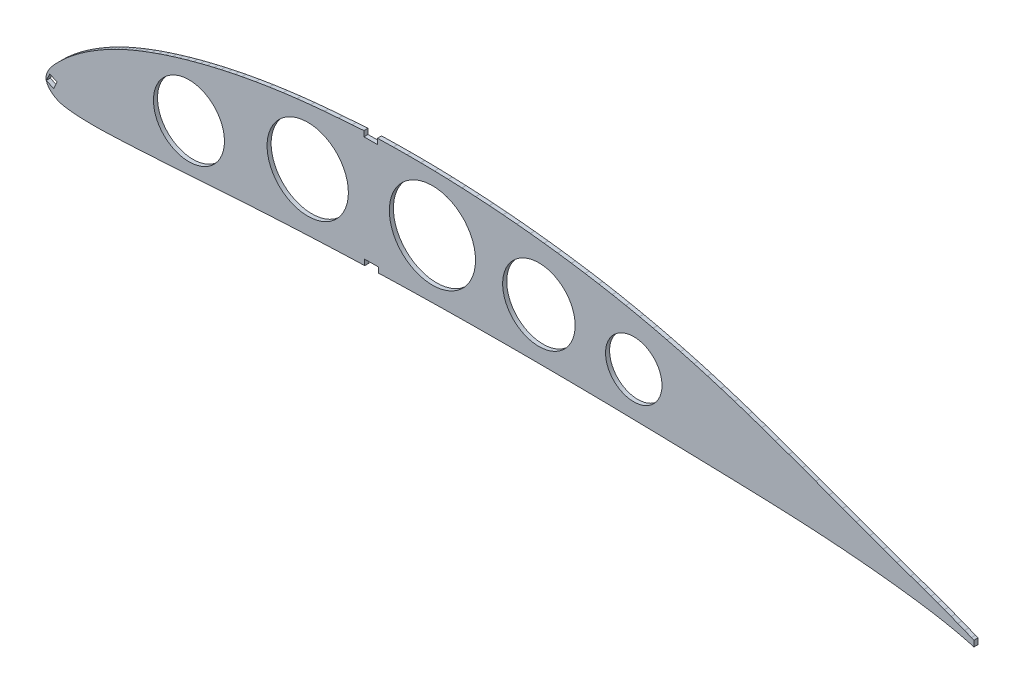
SolidWorks part; units mm, degrees
ref_plane "前视基准面" through (0, 0, 0) normal (0, 0, 1) x (1, 0, 0)
ref_plane "上视基准面" through (0, 0, 0) normal (0, 1, 0) x (1, 0, 0)
ref_plane "右视基准面" through (0, 0, 0) normal (1, 0, 0) x (0, 0, -1)
sketch "Model" plane through (0, 0, 0) normal (0, 0, 1) x (1, 0, 0)
  line L0 (1316.8722, -1.8169) -> (1315.9367, -1.4179)
  line L1 (1315.9367, -1.4179) -> (1313.4384, -0.3986)
  line L2 (1313.4384, -0.3986) -> (1310.9303, 0.599)
  line L3 (1310.9303, 0.599) -> (1308.4518, 1.5565)
  line L4 (1308.4518, 1.5565) -> (1305.9665, 2.4943)
  line L5 (1305.9665, 2.4943) -> (1303.4746, 3.4153)
  line L6 (1303.4746, 3.4153) -> (1300.9782, 4.3234)
  line L7 (1300.9782, 4.3234) -> (1298.4785, 5.2226)
  line L8 (1298.4785, 5.2226) -> (1295.9776, 6.1189)
  line L9 (1295.9776, 6.1189) -> (1293.4748, 7.0143)
  line L10 (1293.4748, 7.0143) -> (1288.4765, 8.8157)
  line L11 (1288.4765, 8.8157) -> (1283.4846, 10.63)
  line L12 (1283.4846, 10.63) -> (1278.4971, 12.4531)
  line L13 (1278.4971, 12.4531) -> (1273.5139, 14.285)
  line L14 (1273.5139, 14.285) -> (1268.5309, 16.1209)
  line L15 (1268.5309, 16.1209) -> (1263.5479, 17.9588)
  line L16 (1263.5479, 17.9588) -> (1258.5629, 19.7958)
  line L17 (1258.5629, 19.7958) -> (1253.6014, 21.6189)
  line L18 (1253.6014, 21.6189) -> (1248.6354, 23.4282)
  line L19 (1248.6354, 23.4282) -> (1243.6635, 25.2137)
  line L20 (1243.6635, 25.2137) -> (1238.6795, 26.9676)
  line L21 (1238.6795, 26.9676) -> (1233.6818, 28.678)
  line L22 (1233.6818, 28.678) -> (1228.6653, 30.337)
  line L23 (1228.6653, 30.337) -> (1223.6274, 31.9348)
  line L24 (1223.6274, 31.9348) -> (1218.677, 33.4313)
  line L25 (1218.677, 33.4313) -> (1213.7069, 34.8574)
  line L26 (1213.7069, 34.8574) -> (1208.7173, 36.2133)
  line L27 (1208.7173, 36.2133) -> (1203.709, 37.4967)
  line L28 (1203.709, 37.4967) -> (1198.682, 38.7079)
  line L29 (1198.682, 38.7079) -> (1193.6383, 39.8455)
  line L30 (1193.6383, 39.8455) -> (1188.5759, 40.9078)
  line L31 (1188.5759, 40.9078) -> (1183.5821, 41.8796)
  line L32 (1183.5821, 41.8796) -> (1178.5767, 42.7787)
  line L33 (1178.5767, 42.7787) -> (1173.5597, 43.6072)
  line L34 (1173.5597, 43.6072) -> (1168.5323, 44.369)
  line L35 (1168.5323, 44.369) -> (1163.4944, 45.0652)
  line L36 (1163.4944, 45.0652) -> (1158.4472, 45.6986)
  line L37 (1158.4472, 45.6986) -> (1153.3918, 46.2704)
  line L38 (1153.3918, 46.2704) -> (1148.3611, 46.7791)
  line L39 (1148.3611, 46.7791) -> (1143.3262, 47.229)
  line L40 (1143.3262, 47.229) -> (1138.2871, 47.619)
  line L41 (1138.2871, 47.619) -> (1133.2448, 47.9481)
  line L42 (1133.2448, 47.9481) -> (1128.1992, 48.2173)
  line L43 (1128.1992, 48.2173) -> (1123.1484, 48.4236)
  line L44 (1123.1484, 48.4236) -> (1118.0953, 48.5679)
  line L45 (1118.0953, 48.5679) -> (1113.0329, 48.6506)
  line L46 (1113.0329, 48.6506) -> (1107.9721, 48.6671)
  line L47 (1107.9721, 48.6671) -> (1102.911, 48.6196)
  line L48 (1102.911, 48.6196) -> (1097.0757, 48.5052)
  line L49 (1092.0788, 48.4515) -> (1087.7366, 48.1323)
  line L50 (1087.7366, 48.1323) -> (1082.6843, 47.7436)
  line L51 (1082.6843, 47.7436) -> (1077.5751, 47.3416)
  line L52 (1077.5751, 47.3416) -> (1072.4731, 46.8624)
  line L53 (1072.4731, 46.8624) -> (1067.3812, 46.3027)
  line L54 (1067.3812, 46.3027) -> (1062.2991, 45.6576)
  line L55 (1062.2991, 45.6576) -> (1057.2298, 44.9249)
  line L56 (1057.2298, 44.9249) -> (1052.1752, 44.1007)
  line L57 (1052.1752, 44.1007) -> (1047.1361, 43.1798)
  line L58 (1047.1361, 43.1798) -> (1044.5687, 42.6726)
  line L59 (1044.5687, 42.6726) -> (1042.0074, 42.1381)
  line L60 (1042.0074, 42.1381) -> (1039.4522, 41.5784)
  line L61 (1039.4522, 41.5784) -> (1036.904, 40.9914)
  line L62 (1036.904, 40.9914) -> (1034.3607, 40.3773)
  line L63 (1034.3607, 40.3773) -> (1031.8245, 39.7358)
  line L64 (1031.8245, 39.7358) -> (1029.2943, 39.0661)
  line L65 (1029.2943, 39.0661) -> (1026.7042, 38.3496)
  line L66 (1026.7042, 38.3496) -> (1024.1241, 37.6017)
  line L67 (1024.1241, 37.6017) -> (1021.5537, 36.8204)
  line L68 (1021.5537, 36.8204) -> (1018.995, 36.0027)
  line L69 (1018.995, 36.0027) -> (1016.448, 35.1485)
  line L70 (1016.448, 35.1485) -> (1013.9135, 34.2538)
  line L71 (1013.9135, 34.2538) -> (1011.3934, 33.3165)
  line L72 (1011.3934, 33.3165) -> (1010.0921, 32.8139)
  line L73 (1010.0921, 32.8139) -> (1008.7953, 32.2981)
  line L74 (1008.7953, 32.2981) -> (1007.5041, 31.7701)
  line L75 (1007.5041, 31.7701) -> (1006.2194, 31.2278)
  line L76 (1006.2194, 31.2278) -> (1004.9412, 30.6723)
  line L77 (1004.9412, 30.6723) -> (1003.6714, 30.1015)
  line L78 (1003.6714, 30.1015) -> (1002.409, 29.5144)
  line L79 (1002.409, 29.5144) -> (1001.0939, 28.8822)
  line L80 (1001.0939, 28.8822) -> (999.7882, 28.2306)
  line L81 (999.7882, 28.2306) -> (998.4918, 27.5617)
  line L82 (998.4918, 27.5617) -> (997.2036, 26.8714)
  line L83 (997.2036, 26.8714) -> (995.9247, 26.1618)
  line L84 (995.9247, 26.1618) -> (994.652, 25.43)
  line L85 (994.652, 25.43) -> (993.3866, 24.6769)
  line L86 (993.3866, 24.6769) -> (992.0269, 23.8382)
  line L87 (992.0269, 23.8382) -> (990.6804, 22.975)
  line L88 (990.6804, 22.975) -> (989.351, 22.0891)
  line L89 (989.351, 22.0891) -> (988.0449, 21.1824)
  line L90 (988.0449, 21.1824) -> (986.7651, 20.2567)
  line L91 (986.7651, 20.2567) -> (985.5187, 19.3137)
  line L92 (985.5187, 19.3137) -> (984.3087, 18.3555)
  line L93 (984.3087, 18.3555) -> (983.5854, 17.7586)
  line L94 (983.5854, 17.7586) -> (982.8716, 17.1523)
  line L95 (982.8716, 17.1523) -> (982.1644, 16.5298)
  line L96 (982.1644, 16.5298) -> (981.4553, 15.8874)
  line L97 (981.4553, 15.8874) -> (980.7424, 15.2201)
  line L98 (980.7424, 15.2201) -> (980.0172, 14.5202)
  line L99 (980.0172, 14.5202) -> (979.2768, 13.7849)
  line L100 (979.2768, 13.7849) -> (978.2816, 12.7607)
  line L101 (978.2816, 12.7607) -> (977.3112, 11.6785)
  line L102 (977.3112, 11.6785) -> (976.4275, 10.5562)
  line L103 (976.4275, 10.5562) -> (975.6938, 9.4063)
  line L104 (975.6938, 9.4063) -> (975.1709, 8.2437)
  line L105 (975.1709, 8.2437) -> (974.9211, 7.083)
  line L106 (974.9211, 7.083) -> (975.0083, 5.9391)
  line L107 (975.0083, 5.9391) -> (975.3491, 5.072)
  line L108 (975.3491, 5.072) -> (975.6362, 4.5621)
  line L109 (975.6362, 4.5621) -> (976.1319, 3.9185)
  line L110 (976.1319, 3.9185) -> (976.7213, 3.3165)
  line L111 (976.7213, 3.3165) -> (977.3826, 2.7689)
  line L112 (977.3826, 2.7689) -> (978.0953, 2.2834)
  line L113 (978.0953, 2.2834) -> (978.8397, 1.8709)
  line L114 (978.8397, 1.8709) -> (979.5112, 1.5721)
  line L115 (979.5112, 1.5721) -> (980.1908, 1.33)
  line L116 (980.1908, 1.33) -> (980.8762, 1.1377)
  line L117 (980.8762, 1.1377) -> (981.5661, 0.9863)
  line L118 (981.5661, 0.9863) -> (982.2612, 0.8678)
  line L119 (982.2612, 0.8678) -> (982.9602, 0.7721)
  line L120 (982.9602, 0.7721) -> (983.6607, 0.6923)
  line L121 (983.6607, 0.6923) -> (984.9141, 0.5713)
  line L122 (984.9141, 0.5713) -> (986.1713, 0.4711)
  line L123 (986.1713, 0.4711) -> (987.4313, 0.3929)
  line L124 (987.4313, 0.3929) -> (988.695, 0.3345)
  line L125 (988.695, 0.3345) -> (989.9593, 0.2932)
  line L126 (989.9593, 0.2932) -> (991.2243, 0.2698)
  line L127 (991.2243, 0.2698) -> (992.4909, 0.2613)
  line L128 (992.4909, 0.2613) -> (993.758, 0.2689)
  line L129 (993.758, 0.2689) -> (995.0236, 0.2885)
  line L130 (995.0236, 0.2885) -> (996.2885, 0.3191)
  line L131 (996.2885, 0.3191) -> (997.5528, 0.3588)
  line L132 (997.5528, 0.3588) -> (998.8164, 0.4055)
  line L133 (998.8164, 0.4055) -> (1000.0811, 0.4572)
  line L134 (1000.0811, 0.4572) -> (1001.345, 0.5129)
  line L135 (1001.345, 0.5129) -> (1002.611, 0.5705)
  line L136 (1002.611, 0.5705) -> (1003.877, 0.6291)
  line L137 (1003.877, 0.6291) -> (1005.1431, 0.6908)
  line L138 (1005.1431, 0.6908) -> (1006.4083, 0.7534)
  line L139 (1006.4083, 0.7534) -> (1007.6745, 0.818)
  line L140 (1007.6745, 0.818) -> (1008.9398, 0.8857)
  line L141 (1008.9398, 0.8857) -> (1010.2062, 0.9553)
  line L142 (1010.2062, 0.9553) -> (1012.7413, 1.1015)
  line L143 (1012.7413, 1.1015) -> (1015.2747, 1.2567)
  line L144 (1015.2747, 1.2567) -> (1017.8083, 1.4179)
  line L145 (1017.8083, 1.4179) -> (1020.3401, 1.5852)
  line L146 (1020.3401, 1.5852) -> (1022.8731, 1.7555)
  line L147 (1022.8731, 1.7555) -> (1025.4051, 1.9278)
  line L148 (1025.4051, 1.9278) -> (1027.9381, 2.101)
  line L149 (1027.9381, 2.101) -> (1030.4721, 2.2722)
  line L150 (1030.4721, 2.2722) -> (1033.0051, 2.4425)
  line L151 (1033.0051, 2.4425) -> (1035.5379, 2.6097)
  line L152 (1035.5379, 2.6097) -> (1038.0707, 2.776)
  line L153 (1038.0707, 2.776) -> (1040.6034, 2.9392)
  line L154 (1040.6034, 2.9392) -> (1043.137, 3.0995)
  line L155 (1043.137, 3.0995) -> (1045.6714, 3.2566)
  line L156 (1045.6714, 3.2566) -> (1050.734, 3.5612)
  line L157 (1050.734, 3.5612) -> (1055.7971, 3.8518)
  line L158 (1055.7971, 3.8518) -> (1060.8596, 4.1274)
  line L159 (1060.8596, 4.1274) -> (1065.9216, 4.389)
  line L160 (1065.9216, 4.389) -> (1070.986, 4.6345)
  line L161 (1070.986, 4.6345) -> (1076.0518, 4.8649)
  line L162 (1076.0518, 4.8649) -> (1081.119, 5.0783)
  line L163 (1081.119, 5.0783) -> (1086.1787, 5.2759)
  line L164 (1086.1787, 5.2759) -> (1091.2377, 5.4556)
  line L165 (1091.2377, 5.4556) -> (1092.3757, 5.4926)
  line L166 (1097.3738, 5.6321) -> (1101.3549, 5.7679)
  line L167 (1101.3549, 5.7679) -> (1106.4141, 5.8985)
  line L168 (1106.4141, 5.8985) -> (1111.4748, 6.014)
  line L169 (1111.4748, 6.014) -> (1116.5377, 6.1115)
  line L170 (1116.5377, 6.1115) -> (1121.5942, 6.1942)
  line L171 (1121.5942, 6.1942) -> (1126.65, 6.2599)
  line L172 (1126.65, 6.2599) -> (1131.7053, 6.3116)
  line L173 (1131.7053, 6.3116) -> (1136.76, 6.3473)
  line L174 (1136.76, 6.3473) -> (1141.8142, 6.37)
  line L175 (1141.8142, 6.37) -> (1146.8709, 6.3786)
  line L176 (1146.8709, 6.3786) -> (1151.9282, 6.3752)
  line L177 (1151.9282, 6.3752) -> (1156.983, 6.3589)
  line L178 (1156.983, 6.3589) -> (1162.0354, 6.3306)
  line L179 (1162.0354, 6.3306) -> (1167.0873, 6.2904)
  line L180 (1167.0873, 6.2904) -> (1172.1388, 6.2391)
  line L181 (1172.1388, 6.2391) -> (1177.1899, 6.1759)
  line L182 (1177.1899, 6.1759) -> (1182.2425, 6.1016)
  line L183 (1182.2425, 6.1016) -> (1187.2958, 6.0163)
  line L184 (1187.2958, 6.0163) -> (1192.3477, 5.921)
  line L185 (1192.3477, 5.921) -> (1197.3982, 5.8148)
  line L186 (1197.3982, 5.8148) -> (1202.4465, 5.7017)
  line L187 (1202.4465, 5.7017) -> (1207.4954, 5.5805)
  line L188 (1207.4954, 5.5805) -> (1212.5441, 5.4533)
  line L189 (1212.5441, 5.4533) -> (1217.5947, 5.321)
  line L190 (1217.5947, 5.321) -> (1222.6461, 5.1848)
  line L191 (1222.6461, 5.1848) -> (1227.6973, 5.0445)
  line L192 (1227.6973, 5.0445) -> (1232.7473, 4.8952)
  line L193 (1232.7473, 4.8952) -> (1237.7947, 4.7331)
  line L194 (1237.7947, 4.7331) -> (1242.8414, 4.5509)
  line L195 (1242.8414, 4.5509) -> (1247.8873, 4.3448)
  line L196 (1247.8873, 4.3448) -> (1252.9329, 4.1067)
  line L197 (1252.9329, 4.1067) -> (1257.9773, 3.8325)
  line L198 (1257.9773, 3.8325) -> (1263.0271, 3.5172)
  line L199 (1263.0271, 3.5172) -> (1268.0723, 3.156)
  line L200 (1268.0723, 3.156) -> (1273.1137, 2.7479)
  line L201 (1273.1137, 2.7479) -> (1278.1513, 2.2899)
  line L202 (1278.1513, 2.2899) -> (1283.1839, 1.7771)
  line L203 (1283.1839, 1.7771) -> (1288.2134, 1.2083)
  line L204 (1288.2134, 1.2083) -> (1293.2388, 0.5806)
  line L205 (1293.2388, 0.5806) -> (1295.767, 0.2397)
  line L206 (1295.767, 0.2397) -> (1298.2924, -0.1221)
  line L207 (1298.2924, -0.1221) -> (1300.8129, -0.5088)
  line L208 (1300.8129, -0.5088) -> (1303.3263, -0.9272)
  line L209 (1303.3263, -0.9272) -> (1305.8333, -1.3814)
  line L210 (1305.8333, -1.3814) -> (1308.3308, -1.8773)
  line L211 (1308.3308, -1.8773) -> (1310.8196, -2.4189)
  line L212 (1310.8196, -2.4189) -> (1313.3442, -3.0219)
  line L213 (1313.3442, -3.0219) -> (1315.8581, -3.6705)
  line L214 (1315.8581, -3.6705) -> (1316.8722, -3.9682)
  line L215 (1316.8722, -3.9682) -> (1316.8722, -1.8169)
  line L216 (976.2906, 8.6672) -> (979.0057, 7.3912)
  line L217 (979.0057, 7.3912) -> (977.7297, 4.6761)
  line L218 (977.7297, 4.6761) -> (975.0423, 5.9391)
  line L219 (975.0423, 5.9391) -> (976.3183, 8.6542)
  line L220 (1097.0898, 46.4863) -> (1092.0927, 46.4515)
  line L221 (1097.3602, 7.5917) -> (1092.3613, 7.5566)
  line L222 (1097.3738, 5.6321) -> (1097.3602, 7.5917)
  line L223 (1092.3757, 5.4926) -> (1092.3613, 7.5566)
  line L224 (1092.0788, 48.4515) -> (1092.0927, 46.4515)
  line L225 (1097.0757, 48.5052) -> (1097.0898, 46.4863)
  circle A0 centre (1071.3704, 25.7688) radius 14.9774
  circle A1 centre (1117.32, 27.6188) radius 15.8803
  circle A2 centre (1156.5586, 25.138) radius 13.3531
  circle A3 centre (1191.5118, 22.0154) radius 10.4013
  circle A4 centre (1027.5976, 19.344) radius 13.0846
extrude "凸台-拉伸1" add sketch "Model" along normal blind 1.5 contours L48 L225 L220 L224 L49 L50 L51 L52 L53 L54 L55 L56 L57 L58 L59 L60 L61 L62 L63 L64 L65 L66 L67 L68 L69 L70 L71 L72 L73 L74 L75 L76 L77 L78 L79 L80 L81 L82 L83 L84 L85 L86 L87 L88 L89 L90 L91 L92 L93 L94 L95
